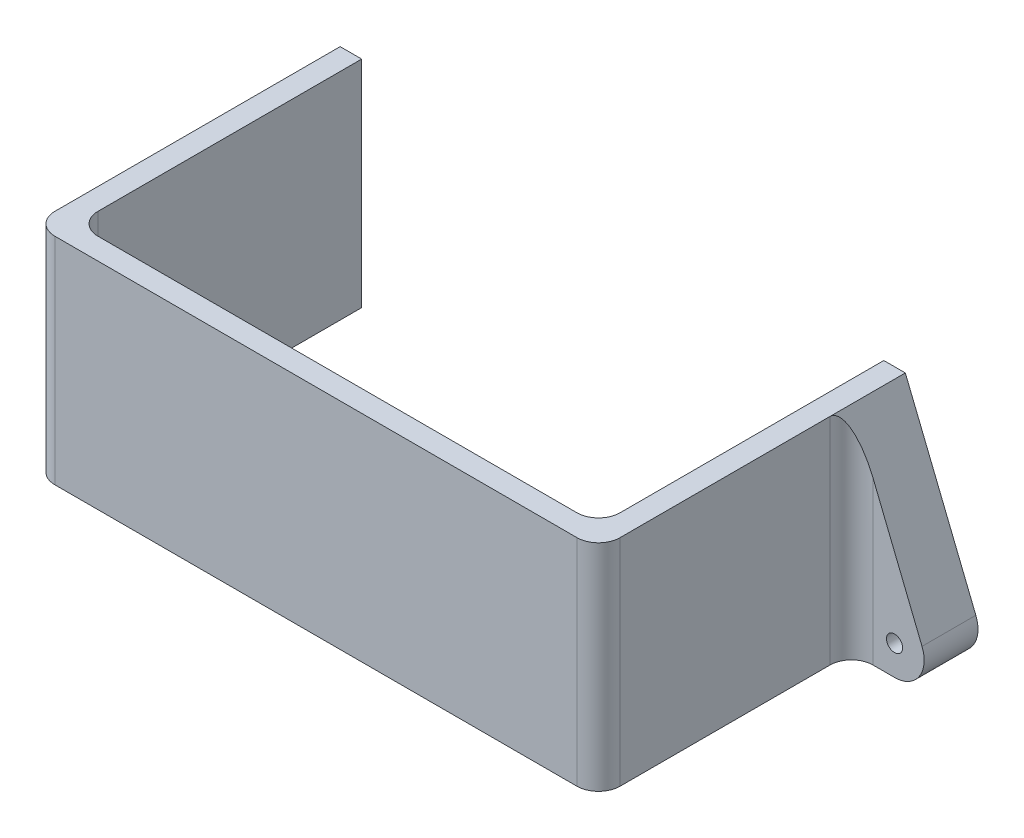
SolidWorks part; units mm, degrees
ref_plane "Front Plane" through (0, 0, 0) normal (0, 0, 1) x (1, 0, 0)
ref_plane "Top Plane" through (0, 0, 0) normal (0, 1, 0) x (1, 0, 0)
ref_plane "Right Plane" through (0, 0, 0) normal (1, 0, 0) x (0, 0, -1)
sketch "Sketch1" plane through (0, 0, 0) normal (0, 1, 0) x (1, 0, 0)
  line L0 (26.25, 13.25) -> (26.25, -15.25)
  line L1 (-24.25, 13.25) -> (24.25, 13.25) construction
  line L2 (-24.25, 13.25) -> (-24.25, -13.25)
  line L3 (-24.25, -13.25) -> (24.25, -13.25)
  line L4 (24.25, 13.25) -> (24.25, -13.25)
  line L5 (0, -13.25) -> (0, 13.25) construction
  line L6 (-24.25, 0) -> (24.25, 0) construction
  line L7 (-26.25, -15.25) -> (26.25, -15.25)
  line L8 (-26.25, 13.25) -> (-26.25, -15.25)
  line L9 (-26.25, 13.25) -> (-24.25, 13.25)
  line L10 (26.25, 13.25) -> (24.25, 13.25)
  point P128 (0, 0)
  dimension "D1" = 48.5
  dimension "D2" = 26.5
  dimension "D3" = 2
extrude "Boss-Extrude1" add sketch "Sketch1" along normal blind 20
fillet "Fillet1" radius 2 4 edges at (-24.25, 10, 13.25) (24.25, 10, 13.25) (26.25, 10, 15.25) (-26.25, 10, 15.25)
sketch "Sketch2" plane through (0, 0, -13.25) normal (0, 0, -1) x (-1, 0, 0)
  line L1 (-26.25, 0) -> (-30.25, 0)
  line L2 (-26.25, 20) -> (-26.25, 0)
  line L3 (-26.25, 20) -> (-26.25, 0)
  line L4 (-32.7999, 3.7797) -> (-26.25, 20)
  arc A0 (-30.25, 0) -> (-32.7999, 3.7797) centre (-30.25, 2.75) cw
  circle A1 centre (-30.25, 2.75) radius 0.75
  point P7 (-33.2816, 0)
  point P8 (-26.25, 16.5087)
  point P10 (0, 0)
  dimension "D2" = 1.5
  dimension "D3" = 2
  dimension "D4" = 4
  dimension "D1" = 0
extrude "Boss-Extrude2" add sketch "Sketch2" against normal blind 5
mirror "Mirror1" about plane through (0, 0, 0) normal (1, 0, 0) of "Boss-Extrude2"
fillet "Fillet2" radius 2 2 edges at (-26.25, 10, -8.25) (26.25, 10, -8.25)
